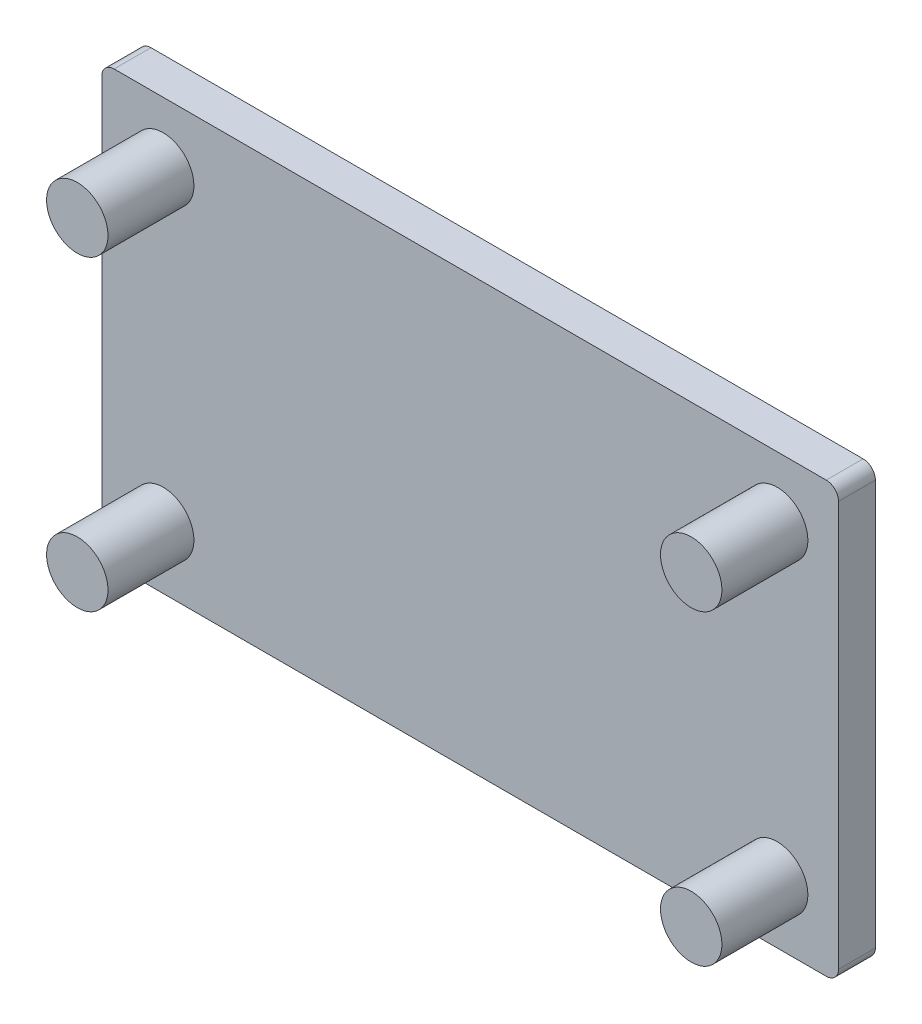
SolidWorks part; units mm, degrees
ref_plane "前基準面" through (0, 0, 0) normal (0, 0, 1) x (1, 0, 0)
ref_plane "上基準面" through (0, 0, 0) normal (0, 1, 0) x (1, 0, 0)
ref_plane "右基準面" through (0, 0, 0) normal (1, 0, 0) x (0, 0, -1)
sketch "草圖1" plane through (0, 0, 0) normal (0, 0, 1) x (1, 0, 0)
  line L0 (0, 15.006) -> (0, -19.994) construction
  line L1 (-30, 15.006) -> (30, 15.006)
  line L2 (-30, 15.006) -> (-30, -19.994)
  line L3 (-30, -19.994) -> (30, -19.994)
  line L4 (30, 15.006) -> (30, -19.994)
  line L5 (-30, -2.494) -> (20, -2.494) construction
  point P4 (0, 15.006)
  point P10 (0, 0)
  point P11 (0, 0)
  point P12 (0, 15.006)
  dimension "D1" = 60
  dimension "D2" = 35
  dimension "D3" = 35
extrude "填料-伸長1" add sketch "草圖1" along normal blind 3
fillet "圓角1" radius 1 4 edges at (-30, -19.994, 1.5) (-30, 15.006, 1.5) (30, -19.994, 1.5) (30, 15.006, 1.5)
sketch "草圖2" plane through (0, 0, 0) normal (0, 0, 1) x (1, 0, 0)
  line L0 (29, 15.006) -> (29, 14.006) construction
  line L1 (29, 14.006) -> (30, 14.006) construction
  line L2 (-30, -18.994) -> (-29, -18.994) construction
  line L3 (-29, -18.994) -> (-29, -19.994) construction
  line L5 (29, 14.006) -> (-29, 14.006)
  line L6 (29, 14.006) -> (29, -18.994)
  line L7 (29, -18.994) -> (-29, -18.994)
  line L8 (-29, 14.006) -> (-29, -18.994)
  dimension "D1" = 33
  dimension "D2" = 58
extrude "除料-伸長1" cut sketch "草圖2" along normal blind 1
fillet "圓角2" radius 0.5 4 edges at (-29, -18.994, 0.5) (-29, 14.006, 0.5) (29, -18.994, 0.5) (29, 14.006, 0.5)
sketch "草圖3" plane through (0, 0, 1) normal (0, 0, -1) x (-1, 0, 0)
  line L0 (-29, 9.006) -> (29, 9.006) construction
  line L3 (-29, -5.5972) -> (29, -5.5972) construction
  line L5 (-29, -18.494) -> (-29, 13.506) construction
  line L6 (29, 13.506) -> (29, -18.494) construction
  line L7 (29, 9.006) -> (29, 14.006) construction
  line L8 (30, 14.006) -> (29, 14.006) construction
  line L18 (-25.7463, -10.4876) -> (-24.4579, -14.3398)
  line L19 (-24.4579, -14.3398) -> (-20.7872, -17.5205)
  line L20 (-20.7872, -17.5205) -> (-23.3909, -14.3398)
  line L21 (-23.3909, -14.3398) -> (-25.7463, -10.4876)
  line L30 (-22.29, -9.2253) -> (-20.1251, -12.6309)
  line L31 (-20.1251, -12.6309) -> (-17.9605, -16.3345)
  line L32 (-17.9605, -16.3345) -> (-20.1251, -11.0924)
  line L33 (-20.1251, -11.0924) -> (-22.29, -9.2253)
  line L34 (29, 13.506) -> (29, -18.494) construction
  line L35 (-25.3773, -8.086) -> (-23.8418, -11.5837)
  line L36 (-23.8418, -11.5837) -> (-18.7134, -17.5506)
  line L37 (-18.7134, -17.5506) -> (-22.7978, -10.17)
  line L38 (-22.7978, -10.17) -> (-22.9002, -10.4774)
  line L40 (-25.3773, -8.086) -> (-22.9002, -10.4774)
  circle A2 centre (16.6059, -11.5904) radius 1
  circle A3 centre (19.7161, -10.0978) radius 1.8
  arc A4 (17.0363, -16.1441) -> (24.9126, -13.0962) centre (22.0402, -17.374) cw
  arc A5 (17.0363, -16.1441) -> (24.9126, -13.0962) centre (23.4777, -21.0888) cw
  text T0 "<b>BADBOY</b>" font "Consolas" height 10.5
  text T1 "<b>TAIWAN</b>" font "Consolas" height 4
  point P17 (-22.29, -9.2253)
  point P29 (-18.3527, -18.1517)
  point P30 (-23.8418, -14.5802)
  point P31 (-21.238, -17.761)
  point P32 (-26.1971, -10.7281)
  dimension "D1" = 5
extrude "填料-伸長2" add sketch "草圖3" along normal blind 1
fillet "圓角5" radius 0.9 2 edges at (-17.6059, -11.5904, 0) (-21.5161, -10.0978, 0)
sketch "草圖4" plane through (0, 0, 3) normal (0, 0, 1) x (1, 0, 0)
  line L0 (-30, 10.006) -> (-25, 10.006) construction
  line L1 (-30, 15.006) -> (-30, -19.994) construction
  line L2 (-25, 10.006) -> (-25, 15.006) construction
  line L3 (-30, 15.006) -> (30, 15.006) construction
  line L4 (-25, -19.994) -> (-25, -14.994) construction
  line L5 (-30, -19.994) -> (30, -19.994) construction
  line L6 (0, 15.006) -> (0, -19.994) construction
  line L7 (29, 15.006) -> (-29, 15.006) construction
  line L8 (-29, -19.994) -> (29, -19.994) construction
  circle A0 centre (-25, 10.006) radius 2.5
  circle A1 centre (-25, -14.994) radius 2.5
  circle A2 centre (25, -14.994) radius 2.5
  circle A3 centre (25, 10.006) radius 2.5
  dimension "D3" = 5
  dimension "D1" = 5
  dimension "D2" = 5
extrude "填料-伸長3" add sketch "草圖4" along normal blind 7
